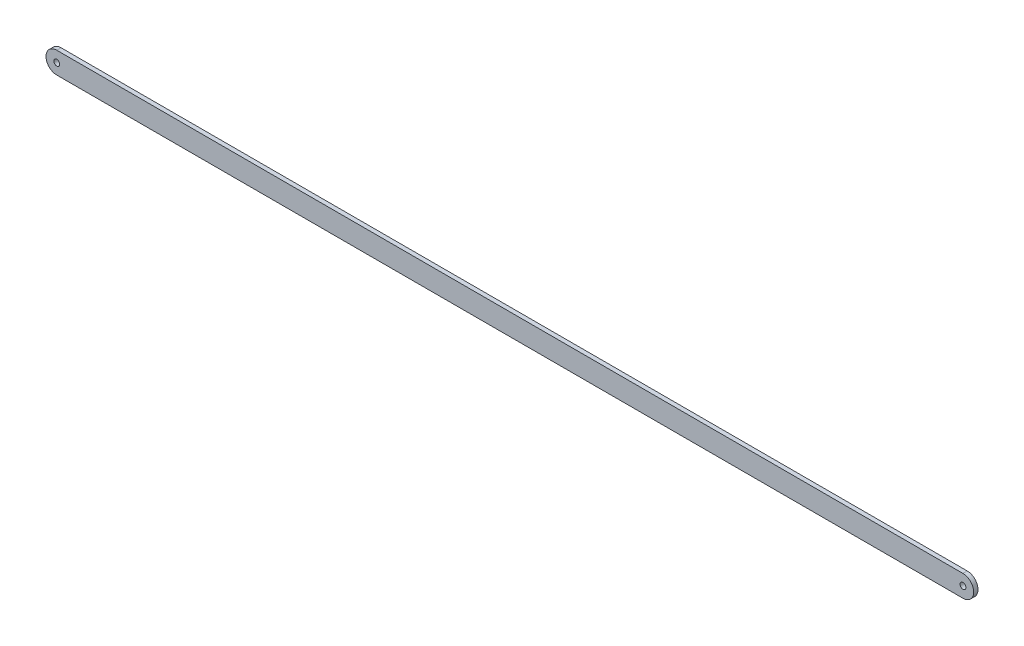
SolidWorks part; units mm, degrees
ref_plane "Front Plane" through (0, 0, 0) normal (0, 0, 1) x (1, 0, 0)
ref_plane "Top Plane" through (0, 0, 0) normal (0, 1, 0) x (1, 0, 0)
ref_plane "Right Plane" through (0, 0, 0) normal (1, 0, 0) x (0, 0, -1)
sketch "Sketch1" plane through (0, 0, 0) normal (0, 0, 1) x (1, 0, 0)
  line L0 (0, 0) -> (0, -50000) construction
  line L1 (-421.355, -10) -> (421.355, -10)
  line L2 (-421.355, -10) -> (-421.355, 10) construction
  line L3 (-421.355, 10) -> (421.355, 10)
  line L4 (421.355, -10) -> (421.355, 10) construction
  line L5 (-421.355, -10) -> (421.355, 10) construction
  line L6 (-421.355, 10) -> (421.355, -10) construction
  arc A0 (-421.355, 10) -> (-421.355, -10) centre (-421.355, 0) ccw
  arc A1 (421.355, 10) -> (421.355, -10) centre (421.355, 0) cw
  circle A2 centre (-421.355, 0) radius 2.75
  circle A3 centre (421.355, 0) radius 2.75
  point P0 (0, 0)
  dimension "D3" = 5.5
  dimension "D1" = 20
  dimension "D2" = 842.71
extrude "Boss-Extrude1" add sketch "Sketch1" along normal blind 4
